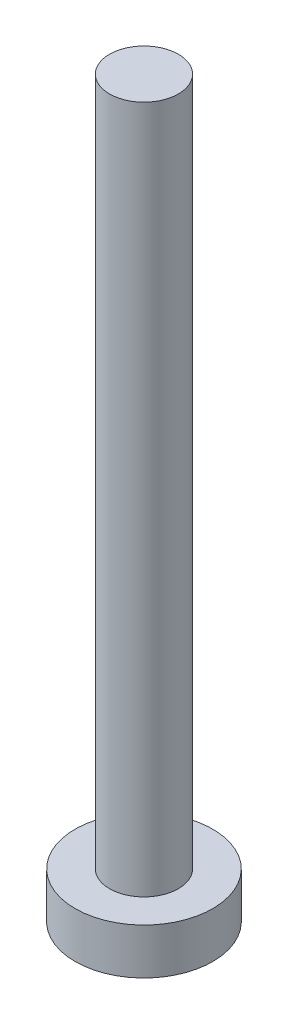
SolidWorks part; units mm, degrees
ref_plane "Front Plane" through (0, 0, 0) normal (0, 0, 1) x (1, 0, 0)
ref_plane "Top Plane" through (0, 0, 0) normal (0, 1, 0) x (1, 0, 0)
ref_plane "Right Plane" through (0, 0, 0) normal (1, 0, 0) x (0, 0, -1)
sketch "Sketch1" plane through (0, 0, 0) normal (0, 1, 0) x (1, 0, 0)
  circle A0 centre (0, 0) radius 1.5
  dimension "D1" = 3
extrude "Boss-Extrude1" add sketch "Sketch1" along normal blind 30
sketch "Sketch2" plane through (0, 0, 0) normal (0, 1, 0) x (1, 0, 0)
  circle A0 centre (0, 0) radius 3
  dimension "D1" = 6
extrude "Boss-Extrude2" add sketch "Sketch2" against normal blind 2
